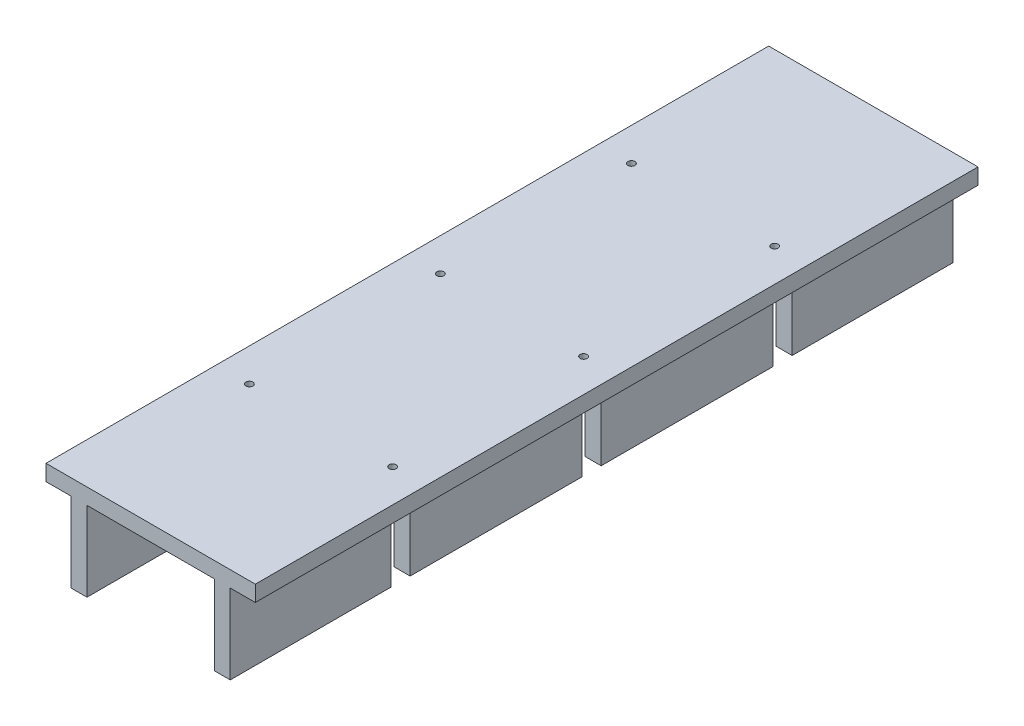
SolidWorks part; units mm, degrees
ref_plane "Front Plane" through (0, 0, 0) normal (0, 0, 1) x (1, 0, 0)
ref_plane "Top Plane" through (0, 0, 0) normal (0, 1, 0) x (1, 0, 0)
ref_plane "Right Plane" through (0, 0, 0) normal (1, 0, 0) x (0, 0, -1)
sketch "Sketch1" plane through (0, 0, 0) normal (0, 0, 1) x (1, 0, 0)
  line L0 (57.15, 0) -> (57.15, 31.75)
  line L1 (0, 0) -> (6.35, 0)
  line L2 (0, 0) -> (0, 31.75)
  line L3 (0, 38.1) -> (63.5, 38.1)
  line L4 (63.5, 0) -> (63.5, 9.525)
  line L5 (6.35, 31.75) -> (57.15, 31.75)
  line L6 (6.35, 0) -> (6.35, 31.75)
  line L7 (57.15, 0) -> (63.5, 0)
  line L14 (63.5, 38.1) -> (73.5, 38.1)
  line L15 (0, 0) -> (0, 38.1) construction
  line L16 (63.5, 9.525) -> (63.5, 31.75)
  line L22 (63.5, 31.75) -> (73.5, 31.75)
  line L23 (63.5, 0) -> (63.5, 38.1) construction
  line L24 (73.5, 38.1) -> (73.5, 31.75)
  line L25 (0, 38.1) -> (-10, 38.1)
  line L27 (0, 31.75) -> (-10, 31.75)
  line L28 (-10, 38.1) -> (-10, 31.75)
  dimension "D1" = 63.5
  dimension "D2" = 38.1
  dimension "D4" = 6.35
  dimension "D5" = 6.35
  dimension "D6" = 83.5
  dimension "D3" = 6.35
extrude "Boss-Extrude1" add sketch "Sketch1" along normal blind 288.29
sketch "Sketch2" plane through (0, 0, 0) normal (-1, 0, 0) x (0, 0, 1)
  line L1 (50.8, 0) -> (0, 0)
  line L2 (50.8, 0) -> (50.8, 12.7)
  line L3 (50.8, 12.7) -> (0, 12.7)
  line L4 (0, 0) -> (0, 12.7)
  dimension "D1" = 12.7
  dimension "D2" = 50.8
extrude "Cut-Extrude1" [suppressed] cut sketch "Sketch2" against normal up to surface (63.5 mm away)
sketch "Sketch3" plane through (0, 38.1, 0) normal (0, 1, 0) x (1, 0, 0)
  line L0 (31.75, 0) -> (31.75, 25.4) construction
  line L1 (73.5, 0) -> (-10, 0) construction
  line L2 (-10, 0) -> (73.5, 0)
  arc A0 (-10, 0) -> (31.75, 25.4) centre (-12.2734, 50.7491) ccw
  arc A1 (31.75, 25.4) -> (73.5, 0) centre (75.7734, 50.7491) ccw
  dimension "D2" = 50.8
  dimension "D3" = 50.8
  dimension "D1" = 25.4
extrude "Boss-Extrude2" [suppressed] add sketch "Sketch3" against normal up to surface (6.35 mm away) separate body
sketch "Sketch4" plane through (63.5, 0, 0) normal (1, 0, 0) x (0, 0, -1)
  line L0 (-288.29, 0) -> (0, 0) construction
  line L1 (-224.155, 0) -> (-216.535, 0)
  line L2 (-224.155, 0) -> (-224.155, 23.8125)
  line L3 (-224.155, 23.8125) -> (-216.535, 23.8125)
  line L4 (-216.535, 0) -> (-216.535, 23.8125)
  line L5 (-288.29, 38.1) -> (0, 38.1) construction
  line L6 (-288.29, 0) -> (-288.29, 31.75) construction
  dimension "D1" = 7.62
  dimension "D2" = 14.2875
  dimension "D3" = 64.135
extrude "Cut-Extrude2" cut sketch "Sketch4" against normal up to surface (63.5 mm away) up to face at (0, 15.875, 144.145)
pattern_linear "LPattern1" count 3 spacing 76.2 along (0, 0, -1) of "Cut-Extrude2"
sketch "Sketch5" plane through (0, 38.1, 0) normal (0, 1, 0) x (1, 0, 0)
  line L0 (3.175, -220.345) -> (60.325, -220.345) construction
  line L1 (73.5, -288.29) -> (-10, -288.29) construction
  line L2 (73.5, -288.29) -> (73.5, 0) construction
  line L3 (-10, -288.29) -> (-10, 0) construction
  circle A0 centre (60.325, -220.345) radius 1.3891
  circle A1 centre (3.175, -220.345) radius 1.3891
  dimension "D1" = 2.7781
  dimension "D2" = 2.7781
  dimension "D3" = 67.945
  dimension "D4" = 13.175
  dimension "D5" = 13.175
extrude "Cut-Extrude3" cut sketch "Sketch5" against normal up to surface (14.2875 mm away) up to face at (60.325, 23.8125, 220.345)
pattern_linear "LPattern2" count 3 spacing 76.2 along (0, 0, -1) of "Cut-Extrude3"
sketch "Sketch6" plane through (63.5, 0, 0) normal (1, 0, 0) x (0, 0, -1)
  line B0 (-216.535, 0) -> (-147.955, 0)
  line B1 (-147.955, 0) -> (-147.955, 23.8125)
  line B2 (-147.955, 23.8125) -> (-140.335, 23.8125)
  line B3 (-140.335, 23.8125) -> (-140.335, 0)
  line B4 (-140.335, 0) -> (-71.755, 0)
  line B5 (-71.755, 0) -> (-71.755, 23.8125)
  line B6 (-71.755, 23.8125) -> (-64.135, 23.8125)
  line B7 (-64.135, 23.8125) -> (-64.135, 0)
  line B8 (-64.135, 0) -> (0, 0)
  line B9 (0, 0) -> (0, 31.75)
  line B10 (0, 31.75) -> (-288.29, 31.75)
  line B11 (-288.29, 31.75) -> (-288.29, 0)
  line B12 (-288.29, 0) -> (-224.155, 0)
  line B13 (-224.155, 0) -> (-224.155, 23.8125)
  line B14 (-224.155, 23.8125) -> (-216.535, 23.8125)
  line B15 (-216.535, 23.8125) -> (-216.535, 0)
sketch_block_instance "Block1-1"
sketch_block "Block1"
sketch "Sketch7" plane through (0, 38.1, 0) normal (0, 1, 0) x (1, 0, 0)
  line B0 (73.5, 0) -> (-10, 0)
  line B1 (-10, 0) -> (-10, -288.29)
  line B2 (-10, -288.29) -> (73.5, -288.29)
  line B3 (73.5, -288.29) -> (73.5, 0)
  circle B4 centre (3.175, -220.345) radius 1.3891
  circle B5 centre (60.325, -220.345) radius 1.3891
  circle B6 centre (60.325, -144.145) radius 1.3891
  circle B7 centre (3.175, -67.945) radius 1.3891
  circle B8 centre (60.325, -67.945) radius 1.3891
  circle B9 centre (3.175, -144.145) radius 1.3891
sketch_block_instance "Block2-1"
sketch_block "Block2"
